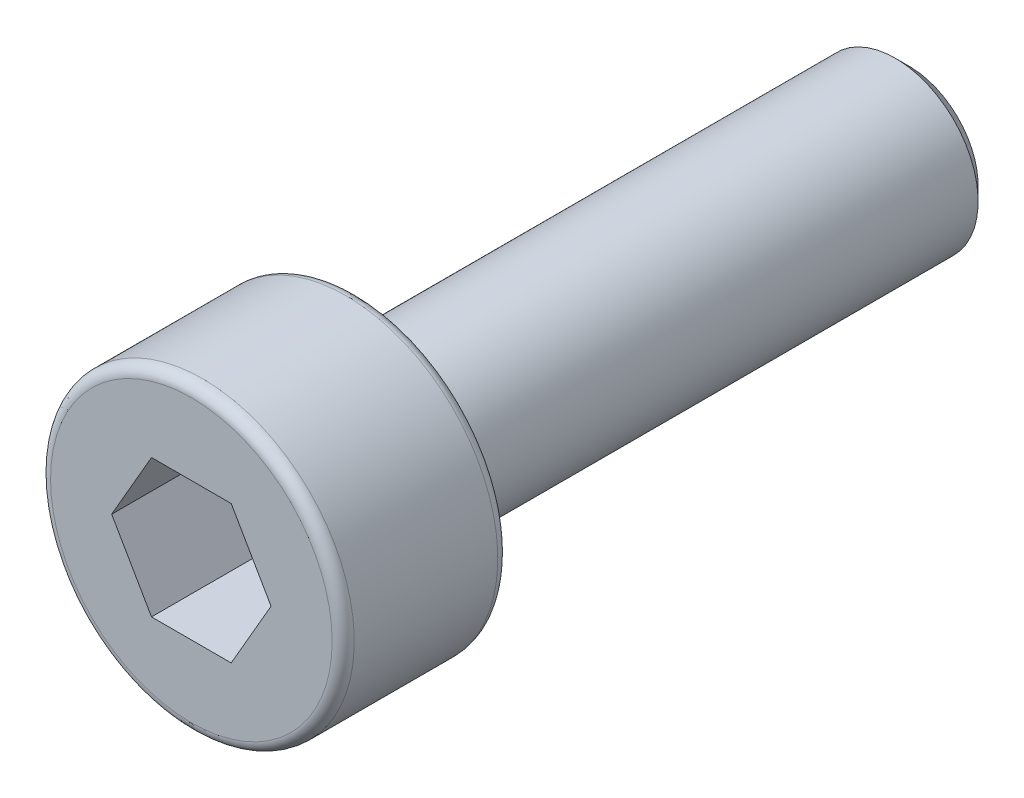
SolidWorks part; units mm, degrees
ref_plane "Front Plane" through (0, 0, 0) normal (0, 0, 1) x (1, 0, 0)
ref_plane "Top Plane" through (0, 0, 0) normal (0, 1, 0) x (1, 0, 0)
ref_plane "Right Plane" through (0, 0, 0) normal (1, 0, 0) x (0, 0, -1)
ref_plane "Plane1" through (0, 0, 13) normal (0, 0, 1) x (1, 0, 0)
sketch "Sketch1" plane through (0, 0, 13) normal (0, 0, 1) x (1, 0, 0)
  circle A0 centre (0, 0) radius 2.75
extrude "Boss-Extrude1" add sketch "Sketch1" against normal blind 3
sketch "Sketch2" plane through (0, 0, 10) normal (0, 0, -1) x (-1, 0, 0)
  circle A0 centre (0, 0) radius 1.5
extrude "Boss-Extrude2" add sketch "Sketch2" along normal blind 10
sketch "Sketch3" plane through (0, 0, 13) normal (0, 0, 1) x (1, 0, 0)
  line L0 (-1.4434, 0) -> (-0.7217, -1.25)
  line L1 (-0.7217, -1.25) -> (0.7217, -1.25)
  line L2 (0.7217, -1.25) -> (1.4434, 0)
  line L3 (1.4434, 0) -> (0.7217, 1.25)
  line L4 (0.7217, 1.25) -> (-0.7217, 1.25)
  line L5 (-0.7217, 1.25) -> (-1.4434, 0)
extrude "Cut-Extrude1" cut sketch "Sketch3" against normal blind 2
chamfer "Chamfer1" distance 0.25 angle 45 1 edges at (-1.5, 0, 0)
fillet "Fillet1" radius 0.2 2 edges at (-2.75, 0, 10) (-2.75, 0, 13)
